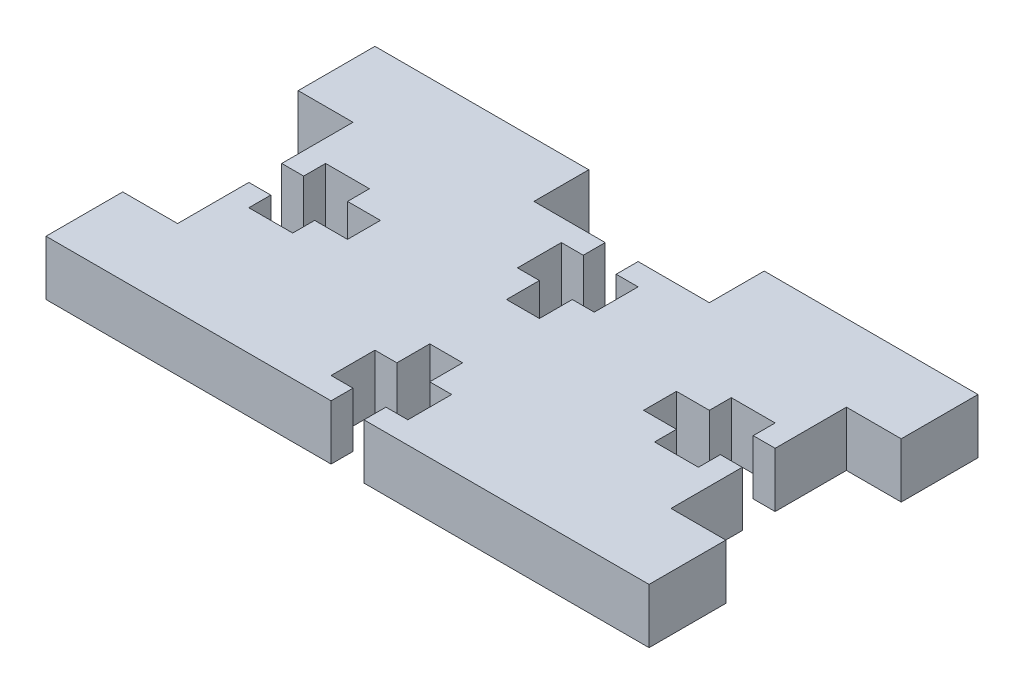
SolidWorks part; units mm, degrees
material "Trupan"
ref_plane "Alzado" through (0, 0, 0) normal (0, 0, 1) x (1, 0, 0)
ref_plane "Planta" through (0, 0, 0) normal (0, 1, 0) x (1, 0, 0)
ref_plane "Vista lateral" through (0, 0, 0) normal (1, 0, 0) x (0, 0, -1)
sketch "Croquis1" plane through (0, 0, 0) normal (0, 1, 0) x (1, 0, 0)
  line L1 (27.5, -15) -> (-27.5, -15)
  line L2 (27.5, -15) -> (27.5, 15)
  line L3 (27.5, 15) -> (-27.5, 15)
  line L4 (-27.5, -15) -> (-27.5, 15)
  line L5 (27.5, -15) -> (-27.5, 15) construction
  line L6 (27.5, 15) -> (-27.5, -15) construction
  point P0 (0, 0)
  dimension "D1" = 55
  dimension "D2" = 30
extrude "Saliente-Extruir1" add sketch "Croquis1" along normal blind 5
sketch "Croquis2" plane through (0, 5, 0) normal (0, 1, 0) x (1, 0, 0)
  line L0 (-27.5, 15) -> (-27.5, -15) construction
  line L5 (-22.5, 8) -> (-27.5, 8)
  line L6 (-22.5, 8) -> (-27.5, 0) construction
  line L7 (-27.5, 0) -> (27.5, 0) construction
  line L8 (27.5, -15) -> (27.5, 15) construction
  line L9 (-22.5, 1.5) -> (-20.5, 1.5)
  line L10 (-20.5, 1.5) -> (-20.5, 3.5)
  line L11 (-20.5, 3.5) -> (-16.5, 3.5)
  line L12 (-16.5, 3.5) -> (-16.5, 1.5)
  line L13 (-16.5, 1.5) -> (-13.5, 1.5)
  line L14 (-13.5, 1.5) -> (-13.5, -1.5)
  line L15 (-22.5, 1.5) -> (-22.5, 8)
  line L16 (-27.5, 8) -> (-27.5, -8)
  line L17 (-22.5, -8) -> (-27.5, 0) construction
  line L18 (-22.5, -1.5) -> (-22.5, -8)
  line L19 (-16.5, -1.5) -> (-13.5, -1.5)
  line L20 (-16.5, -3.5) -> (-16.5, -1.5)
  line L21 (-20.5, -3.5) -> (-16.5, -3.5)
  line L22 (-20.5, -1.5) -> (-20.5, -3.5)
  line L23 (-22.5, -1.5) -> (-20.5, -1.5)
  line L24 (-22.5, -8) -> (-27.5, -8)
  point P0 (-27.5, 0)
  point P19 (-13.5, 0)
  dimension "D1" = 8
  dimension "D2" = 5
  dimension "D3" = 6.5
  dimension "D4" = 2
  dimension "D5" = 2
  dimension "D6" = 4
  dimension "D7" = 3
  dimension "D8" = 1.5
extrude "Cortar-Extruir1" cut sketch "Croquis2" against normal through all
mirror "Simetría1" about plane through (0, 0, 0) normal (1, 0, 0) of "Cortar-Extruir1"
sketch "Croquis3" plane through (0, 5, 0) normal (0, 1, 0) x (1, 0, 0)
  line L0 (0, 15) -> (0, -15) construction
  line L1 (27.5, 15) -> (-27.5, 15) construction
  line L2 (-27.5, -15) -> (27.5, -15) construction
  line L4 (-8, 15) -> (8, 15)
  line L5 (8, 15) -> (8, 10)
  line L6 (8, 10) -> (1.5, 10)
  line L7 (1.5, 10) -> (1.5, 8)
  line L8 (1.5, 8) -> (3.5, 8)
  line L9 (3.5, 8) -> (3.5, 4)
  line L10 (3.5, 4) -> (1.5, 4)
  line L11 (1.5, 4) -> (1.5, 1)
  line L12 (1.5, 1) -> (-1.5, 1)
  line L14 (-1.5, 4) -> (-1.5, 1)
  line L15 (-3.5, 4) -> (-1.5, 4)
  line L16 (-1.5, 8) -> (-3.5, 8)
  line L17 (-3.5, 8) -> (-3.5, 4)
  line L18 (-1.5, 10) -> (-1.5, 8)
  line L19 (-8, 10) -> (-1.5, 10)
  line L20 (-8, 15) -> (-8, 10)
  point P18 (0, 1)
  dimension "D1" = 8
  dimension "D2" = 5
  dimension "D3" = 6.5
  dimension "D4" = 2
  dimension "D5" = 2
  dimension "D6" = 4
  dimension "D7" = 2
  dimension "D8" = 3
extrude "Cortar-Extruir2" cut sketch "Croquis3" against normal through all
sketch "Croquis4" plane through (0, 5, 0) normal (0, 1, 0) x (1, 0, 0)
  line L0 (0, -15) -> (0, 15.5179) construction
  line L1 (-27.5, -15) -> (27.5, -15) construction
  line L2 (1.5, -15) -> (1.5, -13)
  line L3 (1.5, -13) -> (3.5, -13)
  line L4 (3.5, -13) -> (3.5, -9)
  line L5 (3.5, -9) -> (1.5, -9)
  line L6 (1.5, -9) -> (1.5, -6)
  line L7 (1.5, -6) -> (-1.5, -6)
  line L8 (1.5, -15) -> (-1.5, -15)
  line L9 (-1.5, -9) -> (-1.5, -6)
  line L10 (-3.5, -9) -> (-1.5, -9)
  line L11 (-3.5, -13) -> (-3.5, -9)
  line L12 (-1.5, -13) -> (-3.5, -13)
  line L13 (-1.5, -15) -> (-1.5, -13)
  point P13 (0, -6)
  dimension "D1" = 2
  dimension "D2" = 2
  dimension "D3" = 4
  dimension "D4" = 2
  dimension "D5" = 3
  dimension "D6" = 1.5
extrude "Cortar-Extruir3" cut sketch "Croquis4" against normal through all
